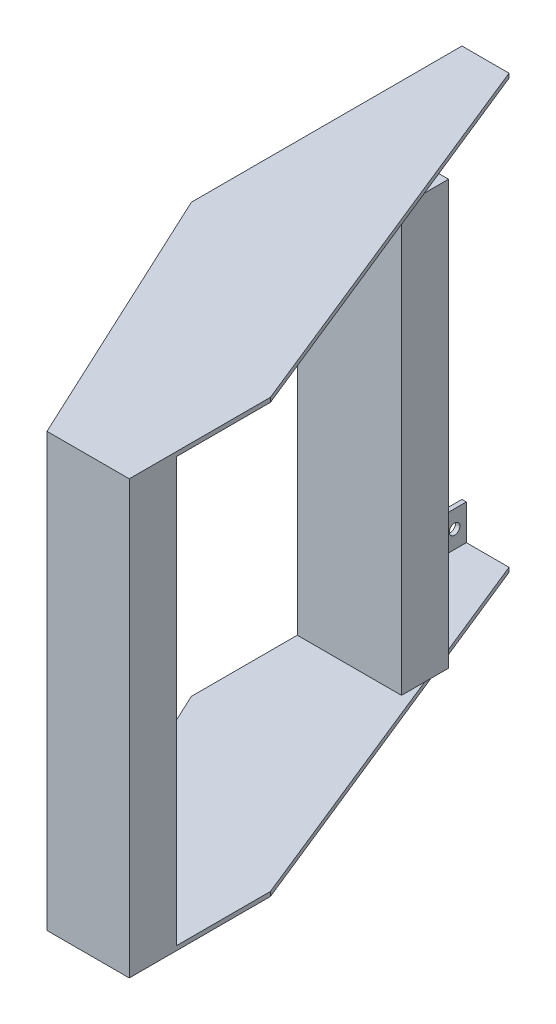
SolidWorks part; units mm, degrees
material "Plain Carbon Steel"
ref_plane "Front Plane" through (0, 0, 0) normal (0, 0, 1) x (1, 0, 0)
ref_plane "Top Plane" through (0, 0, 0) normal (0, 1, 0) x (1, 0, 0)
ref_plane "Right Plane" through (0, 0, 0) normal (1, 0, 0) x (0, 0, -1)
sketch "Sketch1" plane through (0, 0, 0) normal (0, 1, 0) x (1, 0, 0)
  line L5 (23.6865, -292.1) -> (112.522, -292.1)
  line L6 (-112.522, 0) -> (-112.522, 292.1)
  line L7 (-112.522, 292.1) -> (-61.722, 292.1)
  line L8 (112.522, -292.1) -> (112.522, -139.7)
  line L9 (-46.3773, -141.8477) -> (30.7005, 93.8993) construction
  line L10 (-112.522, 292.1) -> (112.522, -292.1) construction
  line L11 (23.6865, -292.1) -> (-112.522, 0)
  line L12 (-61.722, 292.1) -> (112.522, -139.7)
  point P0 (0, 0)
  dimension "D1" = 584.2
  dimension "D2" = 225.044
  dimension "D3" = 152.4
  dimension "D4" = 50.8
extrude "Boss-Extrude1" add sketch "Sketch1" along normal blind 4.7498
sketch "Sketch2" plane through (-112.522, 0, 11.7374) normal (1, 0, 0) x (0, 0, -1)
  line L0 (176.8374, 4.7498) -> (231.2498, 42.8498)
  line L1 (303.8374, 4.7498) -> (176.8374, 4.7498)
  line L2 (303.8374, 4.7498) -> (303.8374, 42.8498)
  line L3 (303.8374, 42.8498) -> (231.2498, 42.8498)
  line L5 (231.2498, 42.8498) -> (176.8374, 4.7498)
  line L6 (303.8374, 23.7998) -> (204.0436, 23.7998) construction
  line L7 (204.0436, 23.7998) -> (303.8374, 23.7998) construction
  circle A0 centre (291.1374, 23.7998) radius 5.715
  circle A1 centre (240.3374, 23.7998) radius 5.715
  dimension "D3" = 12.7
  dimension "D4" = 50.8
  dimension "D5" = 11.43
  dimension "D1" = 127
  dimension "D2" = 38.1
  dimension "D6" = 35
extrude "Boss-Extrude2" add sketch "Sketch2" along normal blind 4.7498 separate body
sketch "Sketch3" plane through (0, 4.7498, 0) normal (0, 1, 0) x (1, 0, 0)
  line L1 (-112.522, 165.1) -> (0, 165.1)
  line L2 (-112.522, 165.1) -> (-112.522, 114.3)
  line L3 (-112.522, 114.3) -> (0, 114.3)
  line L4 (0, 165.1) -> (0, 114.3)
  line L5 (23.6865, -292.1) -> (112.522, -292.1)
  line L6 (23.6865, -292.1) -> (23.6865, -241.3)
  line L7 (23.6865, -241.3) -> (112.522, -241.3)
  line L8 (112.522, -292.1) -> (112.522, -241.3)
  dimension "D1" = 50.8
  dimension "D2" = 50.8
extrude "Boss-Extrude3" add sketch "Sketch3" along normal blind 228.6
ref_plane "Plane1" through (0, 233.3498, 0) normal (0, 1, 0) x (1, 0, 0)
mirror "Mirror1" about plane through (0, 233.3498, 0) normal (0, 1, 0) of bodies 103
